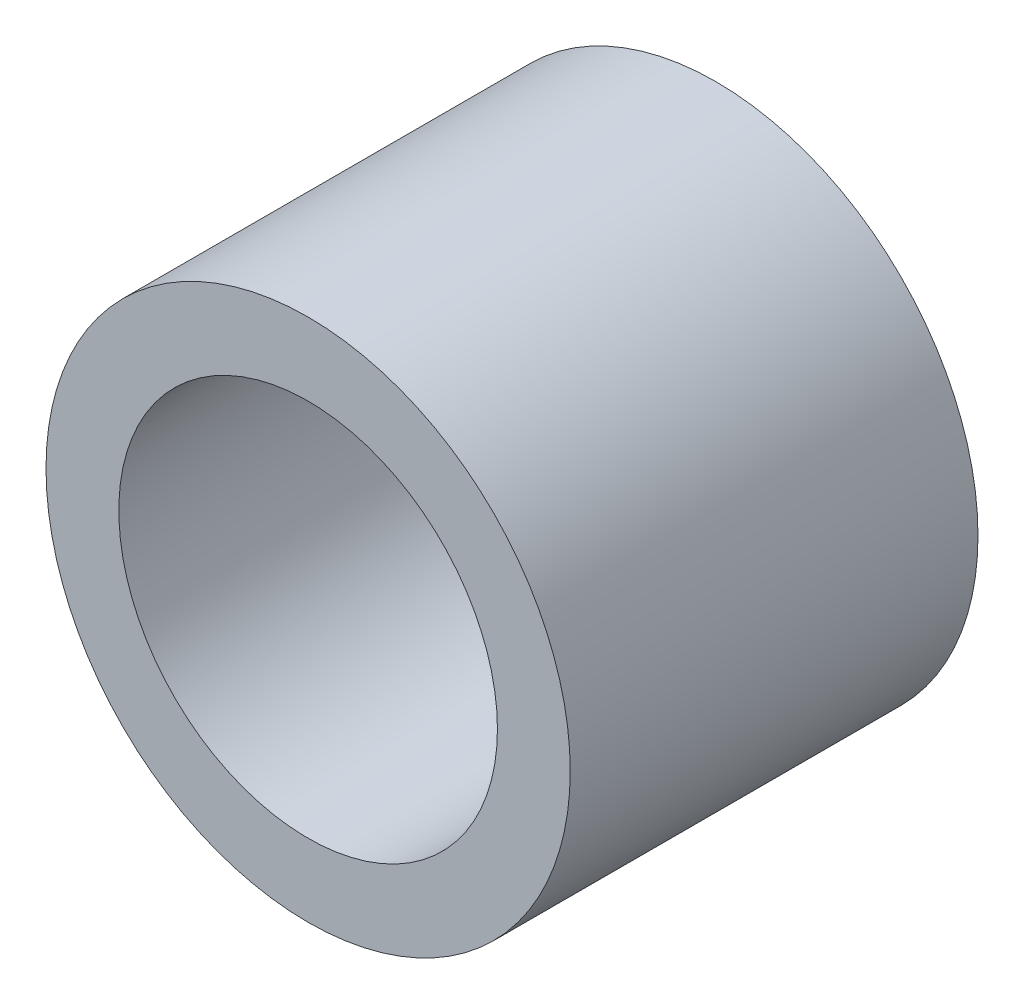
SolidWorks part; units mm, degrees
ref_plane "正面" through (0, 0, 0) normal (0, 0, 1) x (1, 0, 0)
ref_plane "平面" through (0, 0, 0) normal (0, 1, 0) x (1, 0, 0)
ref_plane "右側面" through (0, 0, 0) normal (1, 0, 0) x (0, 0, -1)
sketch "ｽｹｯﾁ1" plane through (0, 0, 0) normal (0, 0, 1) x (1, 0, 0)
  circle A0 centre (0, 0) radius 4.5
  circle A1 centre (0, 0) radius 3.25
  dimension "D1" = 6.5
  dimension "D2" = 9
extrude "ﾎﾞｽ - 押し出し1" add sketch "ｽｹｯﾁ1" along normal blind 7
